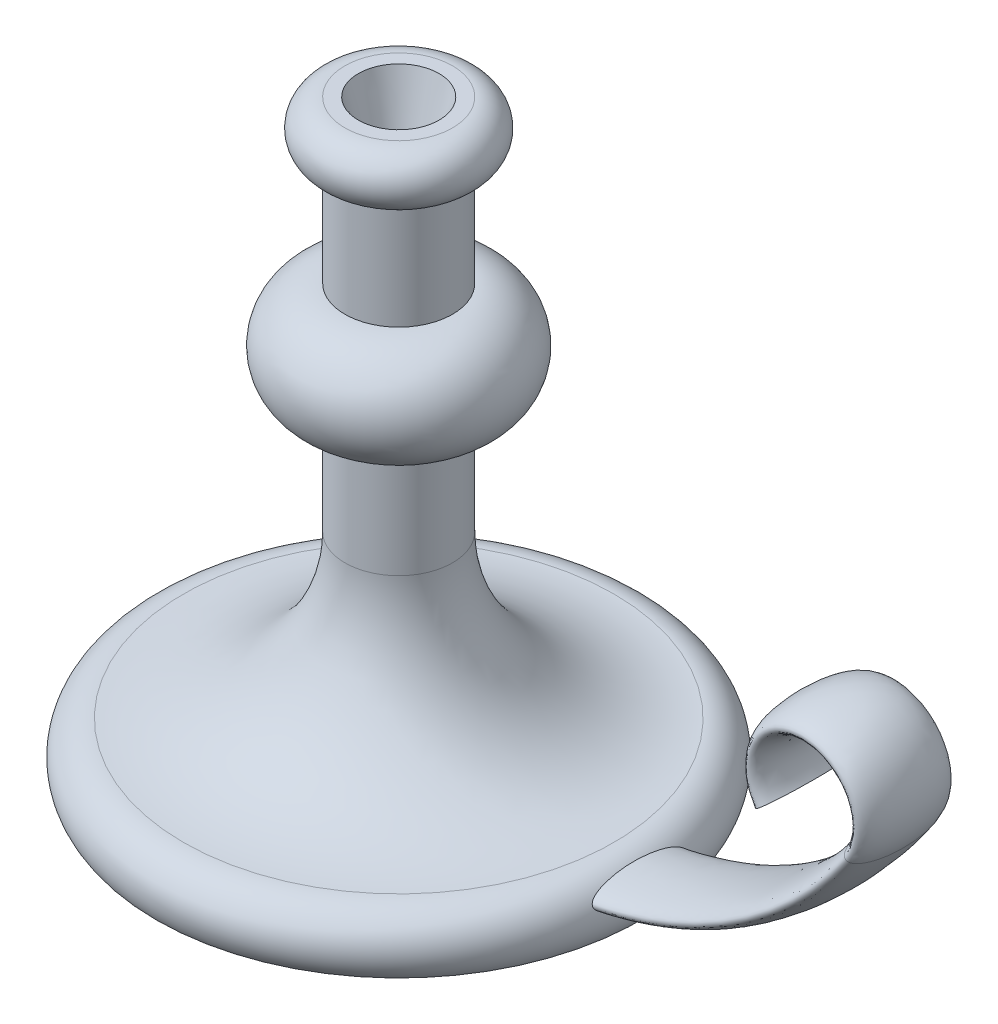
SolidWorks part; units mm, degrees
ref_plane "Front Plane" through (0, 0, 0) normal (0, 0, 1) x (1, 0, 0)
ref_plane "Top Plane" through (0, 0, 0) normal (0, 1, 0) x (1, 0, 0)
ref_plane "Right Plane" through (0, 0, 0) normal (1, 0, 0) x (0, 0, -1)
sketch "Sketch1" plane through (0, 0, 0) normal (0, 0, 1) x (1, 0, 0)
  line L0 (0, 0) -> (0, 220)
  line L1 (0, 220) -> (20, 220)
  line L2 (0, 0) -> (90, 0)
  line L3 (20, 200) -> (20, 160)
  line L4 (20, 120) -> (20, 80)
  arc A0 (20, 220) -> (20, 200) centre (20, 210) cw
  arc A1 (20, 160) -> (20, 120) centre (20, 140) cw
  arc A2 (20, 80) -> (80, 20) centre (80, 80) ccw
  arc A3 (80, 20) -> (90, 0) centre (80, 7.5) cw
  dimension "D4" = 10
  dimension "D5" = 20
  dimension "D7" = 60
  dimension "D8" = 12.5
  dimension "D1" = 220
  dimension "D2" = 90
  dimension "D3" = 20
  dimension "D6" = 40
  dimension "D9" = 80
revolve "Revolve1" add sketch "Sketch1" angle 360 about L0
sketch "Sketch2" plane through (0, 0, 0) normal (0, 0, 1) x (1, 0, 0)
  line L0 (0, 10) -> (60, 10)
  line L1 (0, 227.4356) -> (0, 175.1288) construction
  line L2 (0, 164) -> (0, 92) construction
  line L3 (-90, 0) -> (90, 0) construction
  arc A0 (60, 10) -> (183.5921, 75) centre (60, 160) ccw
  arc A1 (183.5921, 75) -> (150.6342, 75) centre (167.1131, 86.3333) ccw
  dimension "D2" = 150
  dimension "D4" = 20
  dimension "D1" = 60
  dimension "D3" = 65
  dimension "D5" = 10
sketch "Sketch3" plane through (0, 0, 0) normal (1, 0, 0) x (0, 0, -1)
  ellipse E0 centre (0, 10) end of major axis (-17.5, 10) minor radius 5
  dimension "D1" = 10
  dimension "D2" = 35
sweep "Sweep1" add profiles "Sketch3" path "Sketch2"
sketch "Sketch4" plane through (0, 220, 0) normal (0, 1, 0) x (1, 0, 0)
  circle A0 centre (0, 0) radius 15
  dimension "D1" = 30
extrude "Cut-Extrude1" cut sketch "Sketch4" against normal blind 25 draft 15
